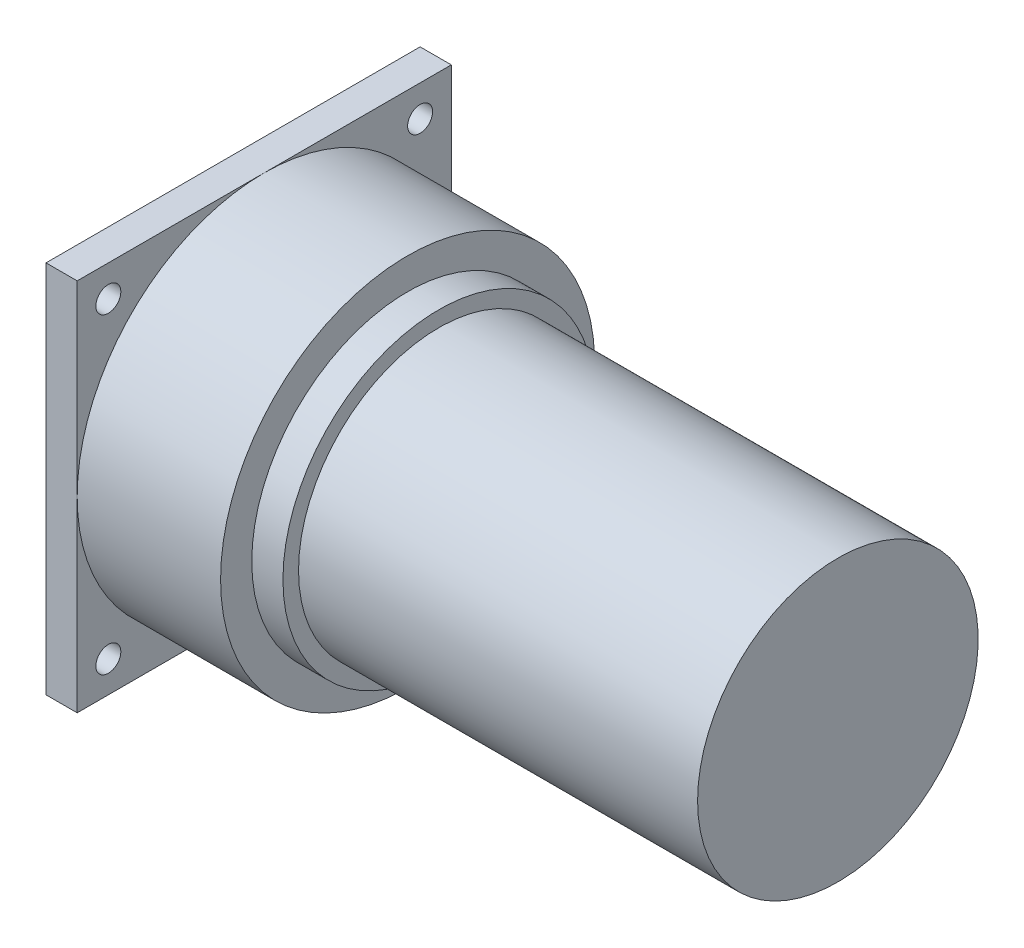
SolidWorks part; units mm, degrees
ref_plane "Front Plane" through (0, 0, 0) normal (0, 0, 1) x (1, 0, 0)
ref_plane "Top Plane" through (0, 0, 0) normal (0, 1, 0) x (1, 0, 0)
ref_plane "Right Plane" through (0, 0, 0) normal (1, 0, 0) x (0, 0, -1)
sketch "Sketch1" plane through (0, 0, 0) normal (0, 1, 0) x (1, 0, 0)
  line L0 (0, 0) -> (0, 4)
  line L1 (0, 4) -> (19, 4)
  line L2 (19, 4) -> (19, 12)
  line L3 (19, 12) -> (22, 12)
  line L4 (22, 12) -> (22, 30)
  line L5 (22, 30) -> (45, 30)
  line L6 (45, 30) -> (45, 25)
  line L7 (45, 25) -> (50, 25)
  line L8 (50, 25) -> (50, 22.5)
  line L9 (50, 22.5) -> (114, 22.5)
  line L10 (114, 22.5) -> (114, 0)
  line L11 (0, 0) -> (114, 0) construction
  line L12 (0, 0) -> (114, 0)
  dimension "D1" = 19
  dimension "D2" = 12
  dimension "D3" = 4
  dimension "D4" = 30
  dimension "D5" = 3
  dimension "D6" = 25
  dimension "D7" = 22.5
  dimension "D8" = 69
  dimension "D9" = 45
  dimension "D10" = 50
revolve "Revolve1" add sketch "Sketch1" angle 360 about L11
ref_plane "Plane1" through (22, 0, 0) normal (-1, 0, 0) x (0, 0, 1)
sketch "Sketch2" plane through (22, 0, 0) normal (-1, 0, 0) x (0, 0, 1)
  line L1 (-30, -30) -> (30, -30)
  line L2 (-30, -30) -> (-30, 30)
  line L3 (-30, 30) -> (30, 30)
  line L4 (30, -30) -> (30, 30)
  circle A0 centre (-25, 25) radius 2
  circle A1 centre (25, 25) radius 2
  circle A2 centre (25, -25) radius 2
  circle A3 centre (-25, -25) radius 2
  point P4 (0, -30)
  point P6 (-30, 0)
  point P15 (-24.7648, 25.2463)
  point P16 (0, 0)
  dimension "D3" = 4
  dimension "D1" = 60
  dimension "D2" = 60
  dimension "D4" = 50
  dimension "D5" = 50
  dimension "D6" = 25
  dimension "D7" = 25
extrude "Boss-Extrude1" add sketch "Sketch2" along normal blind 5
